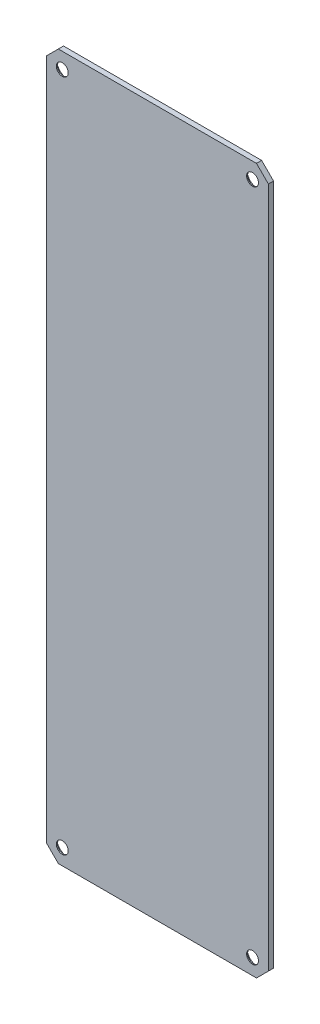
SolidWorks part; units mm, degrees
ref_plane "Front Plane" through (0, 0, 0) normal (0, 0, 1) x (1, 0, 0)
ref_plane "Top Plane" through (0, 0, 0) normal (0, 1, 0) x (1, 0, 0)
ref_plane "Right Plane" through (0, 0, 0) normal (1, 0, 0) x (0, 0, -1)
sketch "Sketch2" plane through (0, 0, 0) normal (0, 0, 1) x (1, 0, 0)
  line L0 (0, 175) -> (3, 178)
  line L1 (3, 0) -> (53, 0)
  line L2 (0, 3) -> (0, 175)
  line L3 (3, 178) -> (53, 178)
  line L4 (56, 3) -> (56, 175)
  line L5 (53, 178) -> (56, 175)
  line L6 (53, 0) -> (56, 3)
  line L7 (0, 3) -> (3, 0)
  point P0 (0, 0)
  point P1 (56, 178)
  point P2 (0, 178)
  point P3 (56, 0)
  dimension "D1" = 56
  dimension "D2" = 178
extrude "Boss-Extrude1" add sketch "Sketch2" along normal blind 1.3
sketch "Sketch4" plane through (0, 0, 1.3) normal (0, 0, 1) x (1, 0, 0)
  line L0 (53, 178) -> (3, 178) construction
  line L1 (0, 175) -> (0, 3) construction
  line L2 (28, 178) -> (28, 0) construction
  line L3 (3, 0) -> (53, 0) construction
  line L4 (0, 89) -> (56, 89) construction
  line L5 (56, 3) -> (56, 175) construction
  circle A0 centre (4, 174) radius 2.667
  circle A1 centre (52, 174) radius 2.667
  circle A2 centre (52, 4) radius 2.667
  circle A3 centre (4, 4) radius 2.667
  dimension "D1" = 5.334
  dimension "D2" = 4
  dimension "D3" = 4
extrude "Cut-Extrude1" cut sketch "Sketch4" against normal blind 2
sketch "Sketch5" plane through (0, 0, 1.3) normal (0, 0, 1) x (1, 0, 0)
  line L0 (28, 178) -> (28, 0) construction
  line L1 (53, 178) -> (3, 178) construction
  line L2 (3, 0) -> (53, 0) construction
  line L3 (0, 89) -> (56, 89) construction
  line L4 (0, 175) -> (0, 3) construction
  line L5 (56, 3) -> (56, 175) construction
  circle A0 centre (4, 174) radius 1.5
  circle A1 centre (4, 174) radius 2.667
  circle A2 centre (52, 174) radius 2.667
  circle A3 centre (52, 174) radius 1.5
  circle A4 centre (52, 4) radius 1.5
  circle A5 centre (52, 4) radius 2.667
  circle A6 centre (4, 4) radius 2.667
  circle A7 centre (4, 4) radius 1.5
  dimension "D1" = 3
extrude "Boss-Extrude2" add sketch "Sketch5" against normal blind 0.254
